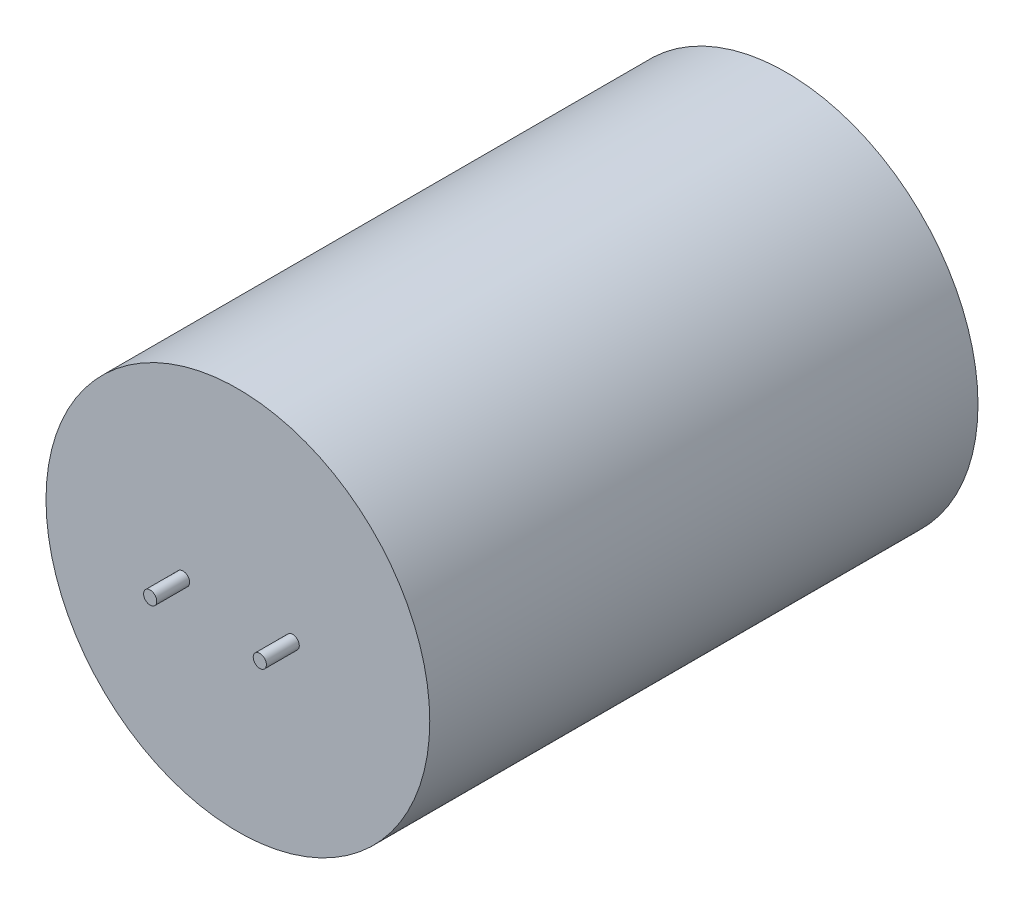
SolidWorks part; units mm, degrees
ref_plane "Спереди" through (0, 0, 0) normal (0, 0, 1) x (1, 0, 0)
ref_plane "Сверху" through (0, 0, 0) normal (0, 1, 0) x (1, 0, 0)
ref_plane "Справа" through (0, 0, 0) normal (1, 0, 0) x (0, 0, -1)
sketch "Эскиз1" plane through (0, 0, 0) normal (0, 0, 1) x (1, 0, 0)
  circle A0 centre (0, 0) radius 17.5
  dimension "D1" = 35
extrude "Вытянуть1" add sketch "Эскиз1" along normal blind 50
sketch "Эскиз2" plane through (0, 0, 50) normal (0, 0, 1) x (1, 0, 0)
  line L0 (0, 17.1388) -> (0, -17.9559) construction
  line L1 (-17.3108, 0) -> (19.9343, 0) construction
  circle A0 centre (-5, 0) radius 0.6
  circle A1 centre (5, 0) radius 0.6
  dimension "D1" = 1.2
  dimension "D2" = 10
extrude "Вытянуть2" add sketch "Эскиз2" along normal blind 3
